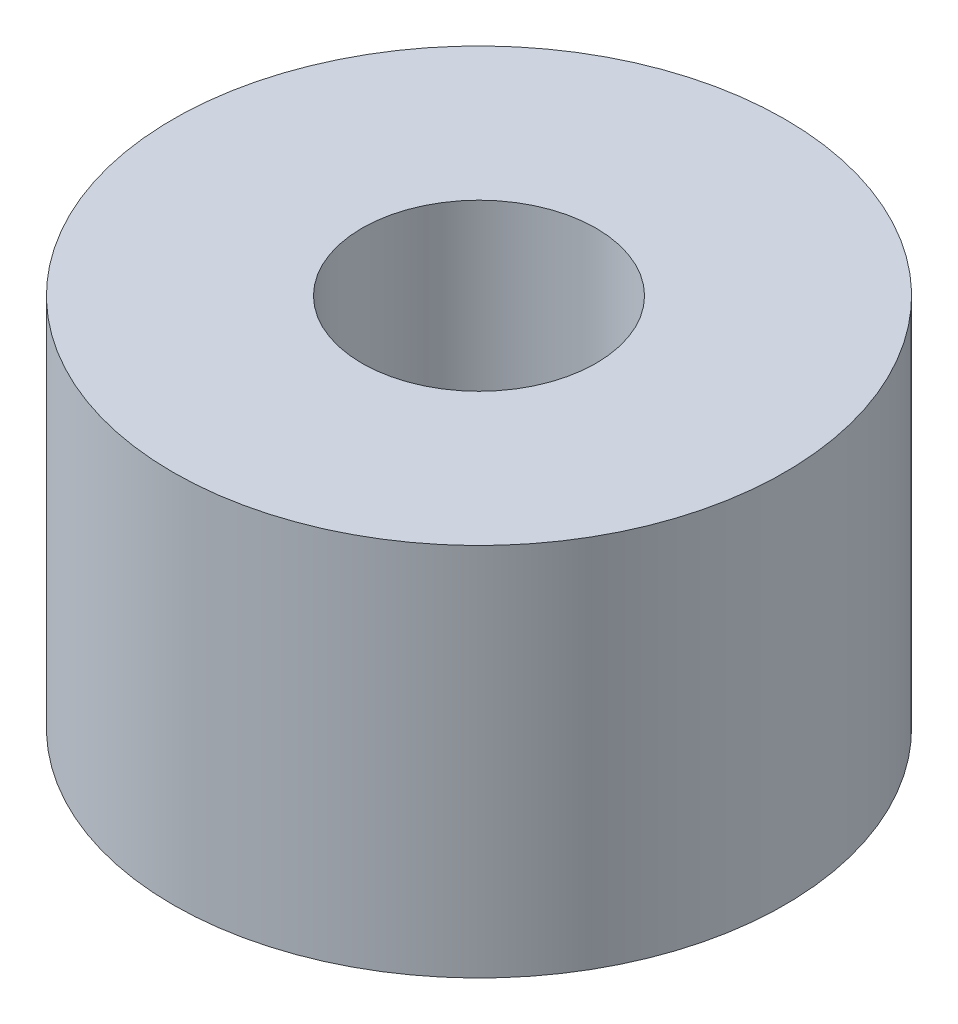
SolidWorks part; units mm, degrees
ref_plane "Front Plane" through (0, 0, 0) normal (0, 0, 1) x (1, 0, 0)
ref_plane "Top Plane" through (0, 0, 0) normal (0, 1, 0) x (1, 0, 0)
ref_plane "Right Plane" through (0, 0, 0) normal (1, 0, 0) x (0, 0, -1)
sketch "Sketch1" plane through (0, 0, 0) normal (0, 1, 0) x (1, 0, 0)
  circle A0 centre (0, 0) radius 12.446
  circle A1 centre (0, 0) radius 4.7625
  dimension "D1" = 24.892
  dimension "D2" = 9.525
extrude "Boss-Extrude1" add sketch "Sketch1" along normal blind 15.24
equation "\"OldSchoolLengthHoles\"= 2.5in'OldSchool > NewSchool"
equation "\"SchoolWidthHoles\"= 1.625in'OldSchool = NewSchool"
equation "\"Angle\"= 40deg'Looks about <= 40deg"
equation "\"Width\"= 2.125in'Pretty sure this is standardized on longboard and skateboard"
equation "\"Length\"= 3in'Will have some variation?"
equation "\"NewSchoolLengthHoles\"= 2.125in'NewSchool Mounting"
equation "\"HoleSize\"= ( 3in / 16 )'hole"
equation "\"Depth\"= 1in / 8'Assuming same depth as a riserplate"
equation "\"KingpinBoltSize\"= 3in / 8"
equation "\"PivotCupDia\"= 0.63in'0.7in (large) 0.626 (small)"
equation "\"PivotCupDepth\"= 12mm'15mm (large) 12mm (small)"
equation "\"PivotCupEndAngle\"= 18deg'Don't Know looks like (I don't even think I used this)"
equation "\"PivotCupInnerDia\"= 0.43in'0.5in (large) 0.43 (small)"
equation "\"BushingDia\"= .98in'Bushing Diameter"
equation "\"BushingDepth\"= .6in'Bushing Depth"
equation "\"D1@Sketch1\"=\"BushingDia\""
equation "\"D2@Sketch1\"=\"KingpinBoltSize\""
equation "\"D1@Boss-Extrude1\"=\"BushingDepth\""
